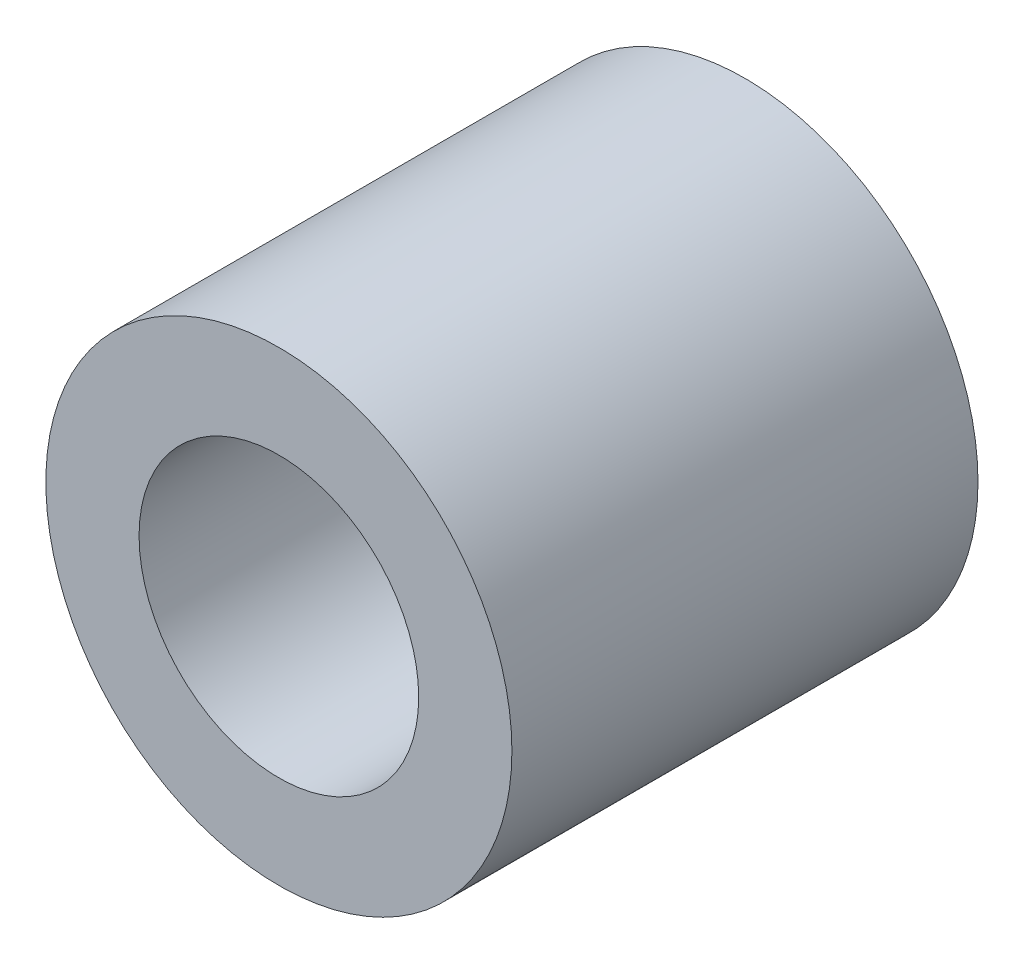
SolidWorks part; units mm, degrees
material "PTFE (general)"
ref_plane "Front Plane" through (0, 0, 0) normal (0, 0, 1) x (1, 0, 0)
ref_plane "Top Plane" through (0, 0, 0) normal (0, 1, 0) x (1, 0, 0)
ref_plane "Right Plane" through (0, 0, 0) normal (1, 0, 0) x (0, 0, -1)
sketch "Sketch1" plane through (0, 0, 0) normal (0, 0, 1) x (1, 0, 0)
  circle A0 centre (0, 0) radius 5
  circle A1 centre (0, 0) radius 3
extrude "Extrude1" add sketch "Sketch1" along normal blind 10
